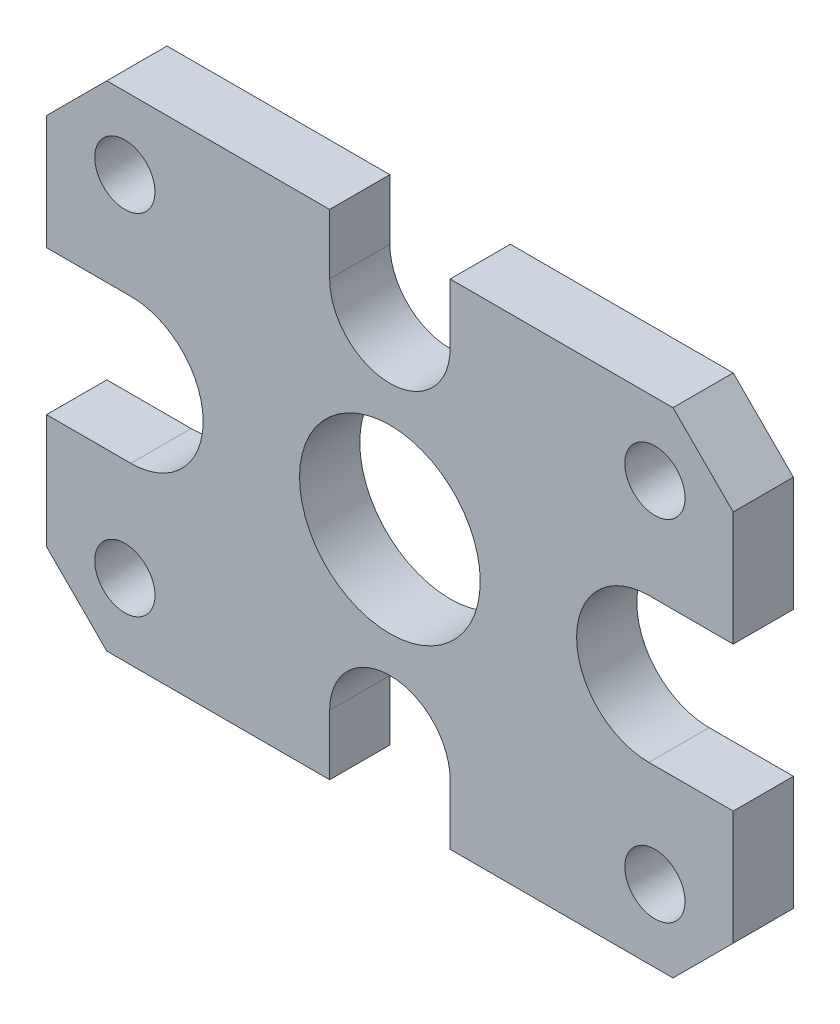
SolidWorks part; units mm, degrees
ref_plane "Front Plane" through (0, 0, 0) normal (0, 0, 1) x (1, 0, 0)
ref_plane "Top Plane" through (0, 0, 0) normal (0, 1, 0) x (1, 0, 0)
ref_plane "Right Plane" through (0, 0, 0) normal (1, 0, 0) x (0, 0, -1)
sketch "Sketch1" plane through (0, 0, 0) normal (0, 0, 1) x (1, 0, 0)
  line L0 (-57, -31) -> (-47, -41)
  line L1 (47, -41) -> (10, -41)
  line L2 (57, -31) -> (57, -12)
  line L3 (47, 41) -> (10, 41)
  line L4 (-57, -31) -> (-57, -12)
  line L7 (-57, 0) -> (57, 0) construction
  line L8 (-57, 31) -> (-47, 41)
  line L9 (0, 41) -> (0, -41) construction
  line L10 (57, -31) -> (47, -41)
  line L11 (57, 31) -> (47, 41)
  line L12 (-10, -41) -> (-10, -31)
  line L13 (10, -31) -> (10, -41)
  line L14 (-10, -41) -> (-47, -41)
  line L15 (10, 31) -> (10, 41)
  line L16 (-10, 41) -> (-10, 31)
  line L17 (-10, 41) -> (-47, 41)
  line L18 (-57, 12) -> (-43, 12)
  line L19 (-43, -12) -> (-57, -12)
  line L20 (43, -12) -> (57, -12)
  line L21 (57, 12) -> (43, 12)
  line L22 (-57, 12) -> (-57, 31)
  line L23 (57, 12) -> (57, 31)
  circle A0 centre (-44, -29) radius 5
  circle A1 centre (-44, 29) radius 5
  circle A2 centre (44, -29) radius 5
  circle A3 centre (44, 29) radius 5
  arc A4 (-10, -31) -> (10, -31) centre (0, -31) cw
  arc A5 (-10, 31) -> (10, 31) centre (0, 31) ccw
  arc A6 (-43, 12) -> (-43, -12) centre (-43, 0) cw
  arc A7 (43, 12) -> (43, -12) centre (43, 0) ccw
  circle A8 centre (0, 0) radius 15
  point P0 (0, 0)
  dimension "D5" = 10
  dimension "D6" = 12
  dimension "D7" = 13
  dimension "D8" = 10
  dimension "D10" = 14
  dimension "D11" = 12
  dimension "D12" = 30
  dimension "D1" = 114
  dimension "D2" = 82
  dimension "D3" = 10
  dimension "D4" = 10
  dimension "D9" = 20
extrude "Boss-Extrude1" add sketch "Sketch1" along normal mid plane 10
